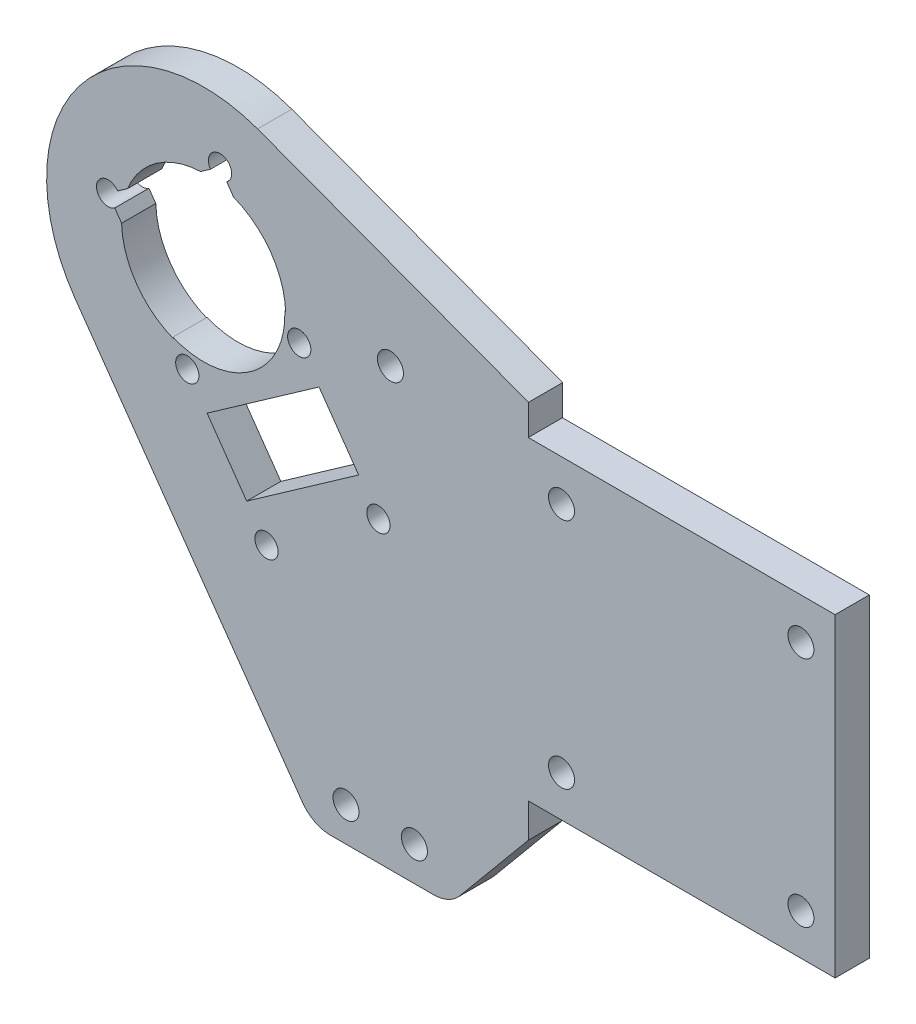
SolidWorks part; units mm, degrees
ref_plane "Plan de face" through (0, 0, 0) normal (0, 0, 1) x (1, 0, 0)
ref_plane "Plan de dessus" through (0, 0, 0) normal (0, 1, 0) x (1, 0, 0)
ref_plane "Plan de droite" through (0, 0, 0) normal (1, 0, 0) x (0, 0, -1)
sketch "Esquisse1" plane through (0, 0, 0) normal (0, 0, 1) x (1, 0, 0)
  line L0 (-14.8092, 33.7997) -> (-20.6609, 29.6912)
  line L1 (-31.1776, 22.3074) -> (-8.0206, -10.6751)
  line L2 (8.3478, 0.8172) -> (2.4961, -3.2913)
  line L3 (-14.8092, 33.7997) -> (8.3478, 0.8172)
  line L4 (-36.0421, 6.6123) -> (-2.7569, -40.6081)
  line L5 (30.2891, 26.5637) -> (-9.322, 41.3694)
  line L6 (30.2505, 22.0854) -> (30.2891, 26.5637)
  line L7 (40.1105, 22.0854) -> (30.2505, 22.0854)
  line L8 (40.1105, -23.9146) -> (40.1105, 22.0854)
  line L9 (30.2505, -23.9146) -> (40.1105, -23.9146)
  line L10 (30.2505, -28.9084) -> (30.2505, -23.9146)
  line L11 (20.2593, -40.9241) -> (30.2505, -28.9084)
  line L12 (1.3299, -42.7274) -> (16.4147, -42.7274)
  line L13 (-27.3577, 32.7831) -> (-24.9156, 29.3048)
  line L14 (-25.9249, 33.7099) -> (-23.4828, 30.2316)
  line L15 (0.6172, -7.0542) -> (3.0593, -10.5325)
  line L16 (2.0085, -6.0774) -> (4.4506, -9.5557)
  line L17 (-2.1689, -6.5666) -> (-8.0206, -10.6751)
  line L18 (-25.3259, 26.4159) -> (-31.1776, 22.3074)
  line L19 (40.1105, -0.9084) -> (-2.6592, -0.9084) construction
  line L20 (-35.12, 45.3254) -> (15.8698, -27.2993) construction
  arc A0 (-2.7569, -40.6081) -> (1.3299, -42.7274) centre (1.3299, -37.7274) ccw
  arc A1 (-9.322, 41.3694) -> (-36.0421, 6.6123) centre (-17.1611, 19.7465) ccw
  arc A2 (16.4147, -42.7274) -> (20.2593, -40.9241) centre (16.4147, -37.7274) ccw
  circle A3 centre (-29.5851, 28.7406) radius 1.9
  circle A4 centre (-21.4009, 34.4867) radius 1.9
  circle A5 centre (-1.4289, -11.3622) radius 1.95
  circle A6 centre (6.7553, -5.616) radius 1.95
  circle A7 centre (10.1041, 21.0535) radius 1.9
  circle A8 centre (3.6086, -37.7436) radius 1.9
  circle A9 centre (13.6086, -37.7309) radius 1.9
  circle A10 centre (35.1105, -17.9146) radius 1.9
  circle A11 centre (35.1105, 16.0852) radius 1.9
  arc A12 (-23.4828, 30.2316) -> (-20.6609, 29.6912) centre (-21.8101, 31.328) ccw
  arc A13 (-27.1316, 33.9448) -> (-27.3577, 32.7831) centre (-26.6413, 33.2465) ccw
  arc A14 (-25.9249, 33.7099) -> (-27.1316, 33.9448) centre (-26.6413, 33.2465) ccw
  arc A15 (3.0593, -10.5325) -> (4.2434, -10.7398) centre (3.755, -10.0441) ccw
  arc A16 (4.2434, -10.7398) -> (4.4506, -9.5557) centre (3.755, -10.0441) ccw
  arc A17 (2.4961, -3.2913) -> (2.0085, -6.0774) centre (3.6453, -4.9281) ccw
  arc A18 (0.6172, -7.0542) -> (-2.1689, -6.5666) centre (-1.0197, -8.2035) ccw
  arc A19 (-25.3259, 26.4159) -> (-24.9156, 29.3048) centre (-26.4751, 28.0527) ccw
  dimension "D3" = 3.8
  dimension "D4" = 5
  dimension "D9" = 5
  dimension "D13" = 6
  dimension "D1" = 46
  dimension "D2" = 9.86
  dimension "D5" = 9.86
  dimension "D6" = 20
  dimension "D7" = 40.3
  dimension "D8" = 5
  dimension "D10" = 54.927
  dimension "D11" = 10
  dimension "D12" = 110
extrude "Boss.-Extru.1" add sketch "Esquisse1" along normal blind 5
sketch "草图1" plane through (0, 0, 5) normal (0, 0, 1) x (1, 0, 0)
  line L0 (-31.1776, 22.3074) -> (-35.9704, 29.1337)
  line L1 (-35.9704, 29.1337) -> (-19.6933, 40.5618)
  line L2 (-19.6933, 40.5618) -> (-14.8092, 33.7997)
  line L3 (-14.8092, 33.7997) -> (-31.1776, 22.3074)
  line L4 (-8.0206, -10.6751) -> (8.3478, 0.8172)
  line L5 (8.3478, 0.8172) -> (13.1844, -6.0715)
  line L6 (13.1844, -6.0715) -> (-3.3844, -17.7045)
  line L7 (-3.3844, -17.7045) -> (-8.0206, -10.6751)
extrude "凸台-拉伸1" add sketch "草图1" against normal blind 5
sketch "草图2" plane through (0, 0, 5) normal (0, 0, 1) x (1, 0, 0)
  line L0 (-31.1776, 22.3074) -> (-3.2307, 17.3084)
  line L1 (8.3478, 0.8172) -> (-14.8092, 33.7997) construction
  line L2 (-3.2307, 17.3084) -> (-19.5991, 5.8161)
  line L3 (-31.1776, 22.3074) -> (-8.0206, -10.6751) construction
  line L4 (-19.5991, 5.8161) -> (-14.8092, 33.7997)
  circle A0 centre (-31.1776, 22.3074) radius 1.7
  circle A1 centre (-14.8092, 33.7997) radius 1.7
  circle A2 centre (-19.5991, 5.8161) radius 1.7
  circle A3 centre (-3.2307, 17.3084) radius 1.7
  circle A4 centre (8.3478, 0.8172) radius 1.7
  circle A5 centre (-8.0206, -10.6751) radius 1.7
  line M1 (-14.8092, 33.7997) -> (8.3478, 0.8172)
  line M2 (8.3478, 0.8172) -> (-2.1689, -6.5666)
  line M3 (-2.1689, -6.5666) -> (-8.0206, -10.6751)
  line M4 (-8.0206, -10.6751) -> (-31.1776, 22.3074)
  line M5 (-31.1776, 22.3074) -> (-25.3259, 26.4159)
  line M7 (-20.6609, 29.6912) -> (-14.8092, 33.7997)
extrude "切除-拉伸1" cut sketch "草图2" against normal blind 5 contours A0 M5 M4 | A1 M1 M7 | A3 M1 | A2 M4 | A5 M4 M3 | A4 M2 M1
sketch "草图3" plane through (0, 0, 5) normal (0, 0, 1) x (1, 0, 0)
  line L0 (-31.1776, 22.3074) -> (-3.2307, 17.3084)
  circle A0 centre (-17.2041, 19.8079) radius 12
  line M2 (-13.8323, 32.4084) -> (-4.2075, 18.6998)
  line M11 (-20.576, 7.2074) -> (-30.2008, 20.916)
  line M13 (-29.7863, 23.2842) -> (-25.3259, 26.4159)
  line M14 (-25.3259, 26.4159) -> (-20.6609, 29.6912)
  line M15 (-20.6609, 29.6912) -> (-16.2005, 32.8228)
extrude "切除-拉伸2" cut sketch "草图3" against normal blind 5 contours A0 M11 | A0 L0 M2 M15 M14 M13 | A0 M15 M13 M14 | A0 M2
sketch "草图4" plane through (0, 0, 5) normal (0, 0, 1) x (1, 0, 0)
  line L0 (-31.1776, 22.3074) -> (-19.5991, 5.8161)
  line L1 (-19.5991, 5.8161) -> (-8.0206, -10.6751)
  line L2 (-8.0206, -10.6751) -> (8.3478, 0.8172)
  line L3 (8.3478, 0.8172) -> (-3.2307, 17.3084)
  line L4 (-3.2307, 17.3084) -> (-14.8092, 33.7997)
  line L5 (-14.8092, 33.7997) -> (-31.1776, 22.3074)
  line L8 (-12.6124, 4.5664) -> (-4.4282, 10.3126)
  line L9 (-4.4282, 10.3126) -> (-0.336, 13.1856)
  line L10 (7.371, 2.2085) -> (-2.2538, 15.9171) construction
  line L11 (-12.6124, 4.5664) -> (-16.7045, 1.6933)
  line L12 (-18.6223, 4.4248) -> (-8.9975, -9.2838) construction
  line L13 (-6.8231, -3.6792) -> (-10.9153, -6.5523)
  line L14 (-10.9153, -6.5523) -> (1.3611, 2.0669)
  line L15 (1.3611, 2.0669) -> (5.4532, 4.94)
  circle A0 centre (-17.2041, 19.8079) radius 11.8755
  circle A1 centre (-31.1776, 22.3074) radius 1.7
  circle A2 centre (-14.8092, 33.7997) radius 1.7
  circle A3 centre (-3.2307, 17.3084) radius 1.7
  circle A4 centre (-19.5991, 5.8161) radius 1.7
  circle A5 centre (-8.0206, -10.6751) radius 1.7
  circle A6 centre (8.3478, 0.8172) radius 1.7
  line M2 (-5.2083, 20.1252) -> (-4.2075, 18.6998)
  line M4 (-2.2538, 15.9171) -> (7.371, 2.2085)
  line M6 (6.9565, -0.1596) -> (-2.1689, -6.5666)
  line M7 (-2.1689, -6.5666) -> (-6.6293, -9.6983)
  line M9 (-8.9975, -9.2838) -> (-18.6223, 4.4248)
  line M11 (-20.576, 7.2074) -> (-21.5768, 8.6329)
extrude "凸台-拉伸3" add sketch "草图4" against normal blind 5 contours A6 L15 L14 L13 A5 M4 M9 M7 M6 | A4 L1 L11 L8 L9 A3 L4 A0 L0 M4 M2 M11
sketch "草图5" plane through (0, 0, 5) normal (0, 0, 1) x (1, 0, 0)
  line L0 (40.1105, 22.0854) -> (37.3018, 22.0854)
  line L1 (40.1105, 22.0854) -> (75.1105, 22.0854)
  line L2 (37.3018, 22.0854) -> (40.1105, 22.0854)
  line L3 (40.1105, -23.9146) -> (75.1105, -23.9146)
  line L4 (75.1105, 22.0854) -> (75.1105, -23.9146)
  line L5 (40.1105, 22.0854) -> (30.2505, 22.0854) construction
  line L6 (37.3018, 22.0854) -> (37.3018, -23.9146)
  line L7 (30.2505, -23.9146) -> (40.1105, -23.9146) construction
  line L8 (37.3018, -23.9146) -> (40.1105, -23.9146)
  line L9 (37.3018, -23.9146) -> (40.1105, -23.9146)
  line L10 (40.1105, -23.9146) -> (40.0809, -24.0539)
  line M34 (40.1105, -23.9146) -> (40.1105, 22.0854)
extrude "凸台-拉伸4" add sketch "草图5" against normal blind 5 contours L4 L1 L3 M34
sketch "草图6" plane through (0, 0, 5) normal (0, 0, 1) x (1, 0, 0)
  circle A0 centre (35.1105, 16.0852) radius 1.9
  circle A1 centre (70.1105, 16.0852) radius 1.9
  circle A2 centre (35.1105, -17.9146) radius 1.9
  circle A3 centre (70.1105, -17.9146) radius 1.9
  point P20 (70.1105, 16.0852)
  point P21 (70.1105, -17.9146)
extrude "切除-拉伸3" cut sketch "草图6" against normal blind 5
